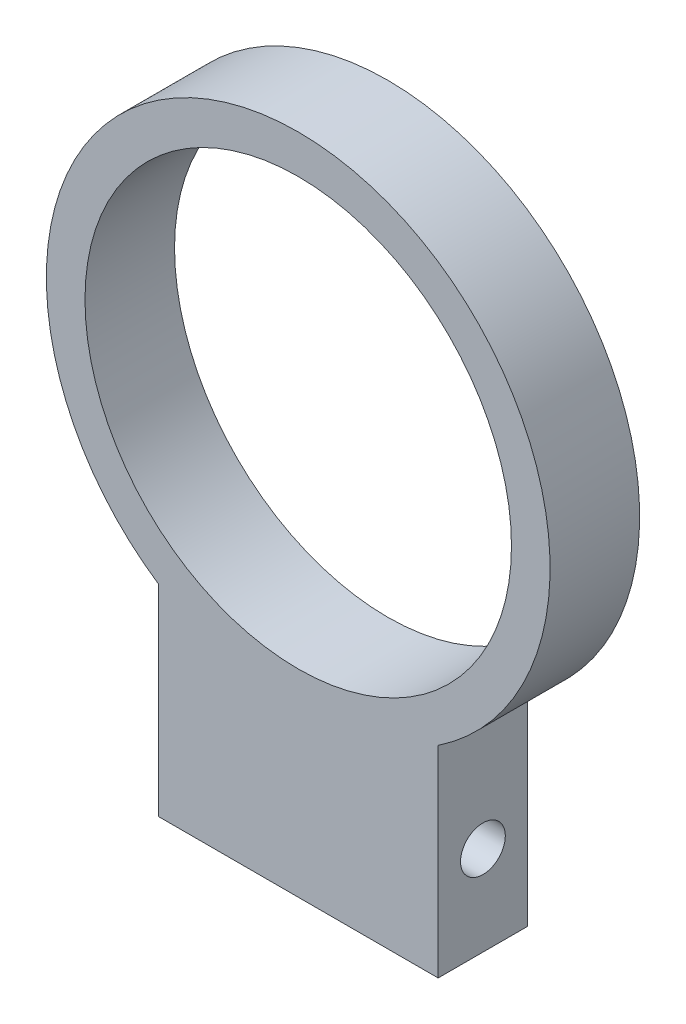
SolidWorks part; units mm, degrees
ref_plane "정면" through (0, 0, 0) normal (0, 0, 1) x (1, 0, 0)
ref_plane "윗면" through (0, 0, 0) normal (0, 1, 0) x (1, 0, 0)
ref_plane "우측면" through (0, 0, 0) normal (1, 0, 0) x (0, 0, -1)
sketch "스케치1" plane through (0, 0, 0) normal (0, 0, 1) x (1, 0, 0)
  line L0 (0, 30.5723) -> (0, -36.5734) construction
  line L1 (-12.5, -18.7083) -> (-12.5, -36.7083)
  line L2 (-12.5, -36.7083) -> (12.5, -36.7083)
  line L3 (12.5, -18.7083) -> (12.5, -36.7083)
  arc A0 (12.5, -18.7083) -> (-12.5, -18.7083) centre (0, 0) ccw
  circle A1 centre (0, 0) radius 19.05
  point P11 (0, -36.7083)
  dimension "D1" = 45
  dimension "D2" = 38.1
  dimension "D3" = 25
  dimension "D4" = 18
extrude "보스-돌출1" add sketch "스케치1" along normal blind 8
sketch "스케치2" plane through (-12.5, 0, 0) normal (-1, 0, 0) x (0, 0, 1)
  line L0 (8, -36.7083) -> (0, -36.7083) construction
  circle A0 centre (4, -28.7083) radius 2
  point P2 (4, -36.7083)
  dimension "D1" = 4
  dimension "D2" = 8
extrude "컷-돌출1" cut sketch "스케치2" against normal up to next
